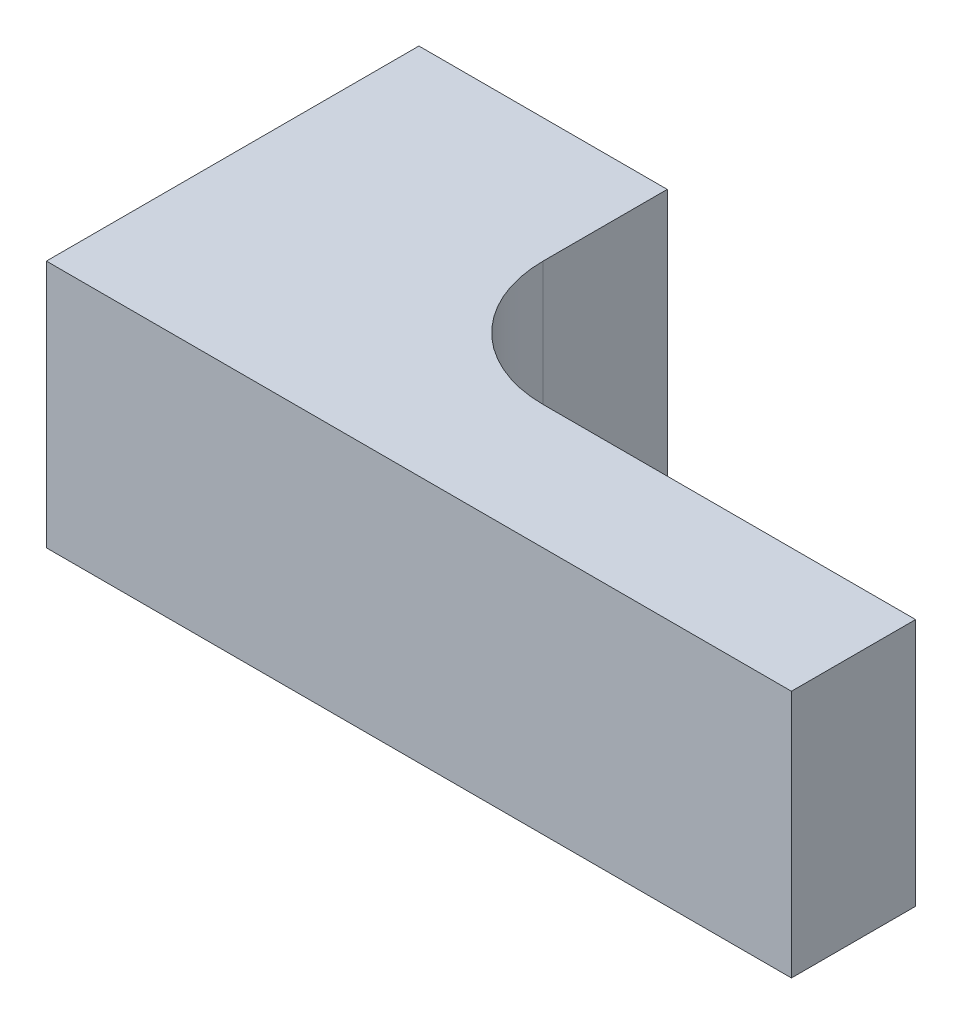
SolidWorks part; units mm, degrees
ref_plane "Přední rovina" through (0, 0, 0) normal (0, 0, 1) x (1, 0, 0)
ref_plane "Horní rovina" through (0, 0, 0) normal (0, 1, 0) x (1, 0, 0)
ref_plane "Pravá rovina" through (0, 0, 0) normal (1, 0, 0) x (0, 0, -1)
sketch "Sketch2" plane through (0, 0, 0) normal (0, 1, 0) x (1, 0, 0)
  line L0 (0, 0) -> (0, -10)
  line L1 (10, -20) -> (40, -20)
  line L2 (40, -20) -> (40, -30)
  line L3 (40, -30) -> (-20, -30)
  line L4 (-20, -30) -> (-20, 0)
  line L5 (-20, 0) -> (0, 0)
  arc A0 (0, -10) -> (10, -20) centre (10, -10) ccw
  dimension "D2" = 10
  dimension "D1" = 20
  dimension "D3" = 30
  dimension "D4" = 10
  dimension "D5" = 10
extrude "Boss-Extrude1" add sketch "Sketch2" along normal blind 20
equation "\"R\"= 10"
equation "\"D2@Sketch2\"=\"R\""
equation "\"D1@Sketch2\"=\"R\" *2"
equation "\"D3@Sketch2\"=\"R\" * 3"
equation "\"D5@Sketch2\"=\"R\""
equation "\"D4@Sketch2\"=\"R\""
